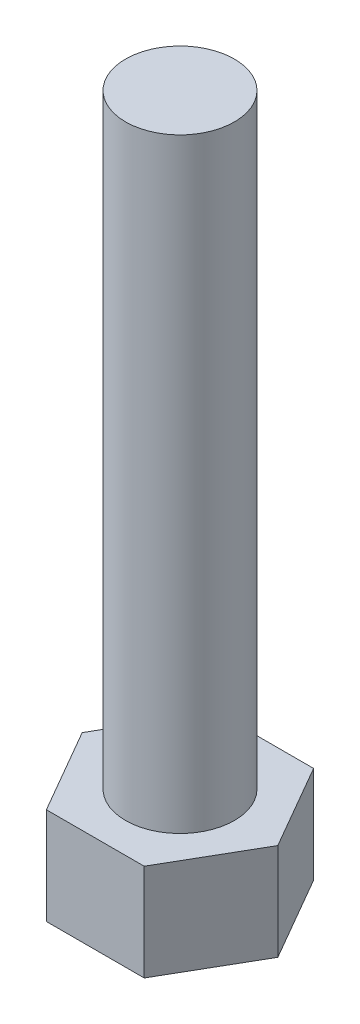
SolidWorks part; units mm, degrees
ref_plane "Front Plane" through (0, 0, 0) normal (0, 0, 1) x (1, 0, 0)
ref_plane "Top Plane" through (0, 0, 0) normal (0, 1, 0) x (1, 0, 0)
ref_plane "Right Plane" through (0, 0, 0) normal (1, 0, 0) x (0, 0, -1)
sketch "Sketch1" plane through (0, 0, 0) normal (0, 1, 0) x (1, 0, 0)
  line L1 (2.0207, -3.5) -> (4.0415, 0)
  line L2 (4.0415, 0) -> (2.0207, 3.5)
  line L3 (2.0207, 3.5) -> (-2.0207, 3.5)
  line L4 (-2.0207, 3.5) -> (-4.0415, 0)
  line L5 (-4.0415, 0) -> (-2.0207, -3.5)
  line L6 (-2.0207, -3.5) -> (2.0207, -3.5)
  circle A0 centre (0, 0) radius 3.5 construction
  dimension "D1" = 7
extrude "Boss-Extrude2" add sketch "Sketch1" along normal blind 4
sketch "Sketch2" plane through (0, 4, 0) normal (0, 1, 0) x (1, 0, 0)
  circle A0 centre (0, 0) radius 2.25
  dimension "D1" = 4.5
extrude "Boss-Extrude3" add sketch "Sketch2" along normal blind 25
